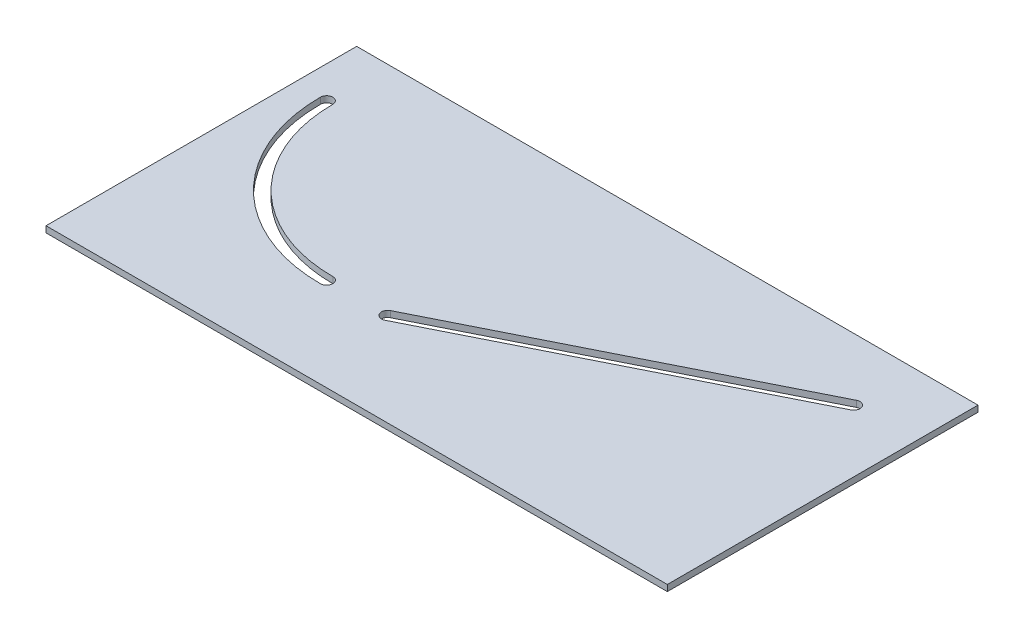
SolidWorks part; units mm, degrees
ref_plane "Plan de face" through (0, 0, 0) normal (0, 0, 1) x (1, 0, 0)
ref_plane "Plan de dessus" through (0, 0, 0) normal (0, 1, 0) x (1, 0, 0)
ref_plane "Plan de droite" through (0, 0, 0) normal (1, 0, 0) x (0, 0, -1)
sketch "Esquisse1" plane through (0, 0, 0) normal (0, 0, 1) x (1, 0, 0)
  line L1 (0, 0) -> (2000, 0)
  line L2 (0, 0) -> (0, 20)
  line L3 (0, 20) -> (2000, 20)
  line L4 (2000, 0) -> (2000, 20)
  dimension "D1" = 2000
  dimension "D2" = 20
extrude "Boss.-Extru.1" add sketch "Esquisse1" along normal blind 1000
sketch "Esquisse2" plane through (0, 20, 0) normal (0, 1, 0) x (1, 0, 0)
  line L0 (1800, -200) -> (800, -700) construction
  line L1 (1808.9443, -217.8885) -> (808.9443, -717.8885)
  line L2 (1791.0557, -182.1115) -> (791.0557, -682.1115)
  line L3 (2000, 0) -> (0, 0) construction
  line L4 (2000, -1000) -> (2000, 0) construction
  line L5 (603.2453, -700) -> (603.2453, -200) construction
  line L6 (603.2453, -200) -> (103.2453, -200) construction
  arc A0 (1808.9443, -217.8885) -> (1791.0557, -182.1115) centre (1800, -200) ccw
  arc A1 (791.0557, -682.1115) -> (808.9443, -717.8885) centre (800, -700) ccw
  arc A2 (103.2453, -200) -> (603.2453, -700) centre (603.2453, -200) ccw construction
  arc A3 (83.2453, -200) -> (603.2453, -720) centre (603.2453, -200) ccw
  arc A4 (123.2453, -200) -> (603.2453, -680) centre (603.2453, -200) ccw
  arc A5 (123.2453, -200) -> (83.2453, -200) centre (103.2453, -200) ccw
  arc A6 (603.2453, -720) -> (603.2453, -680) centre (603.2453, -700) ccw
  point P2 (1300, -450)
  point P10 (249.6919, -553.5534)
  dimension "D3" = 20
  dimension "D6" = 20
  dimension "D9" = 500
  dimension "D1" = 200
  dimension "D2" = 200
  dimension "D4" = 1000
  dimension "D5" = 500
  dimension "D7" = 90
  dimension "D8" = 200
extrude "Enlèv. mat.-Extru.1" cut sketch "Esquisse2" against normal through all
